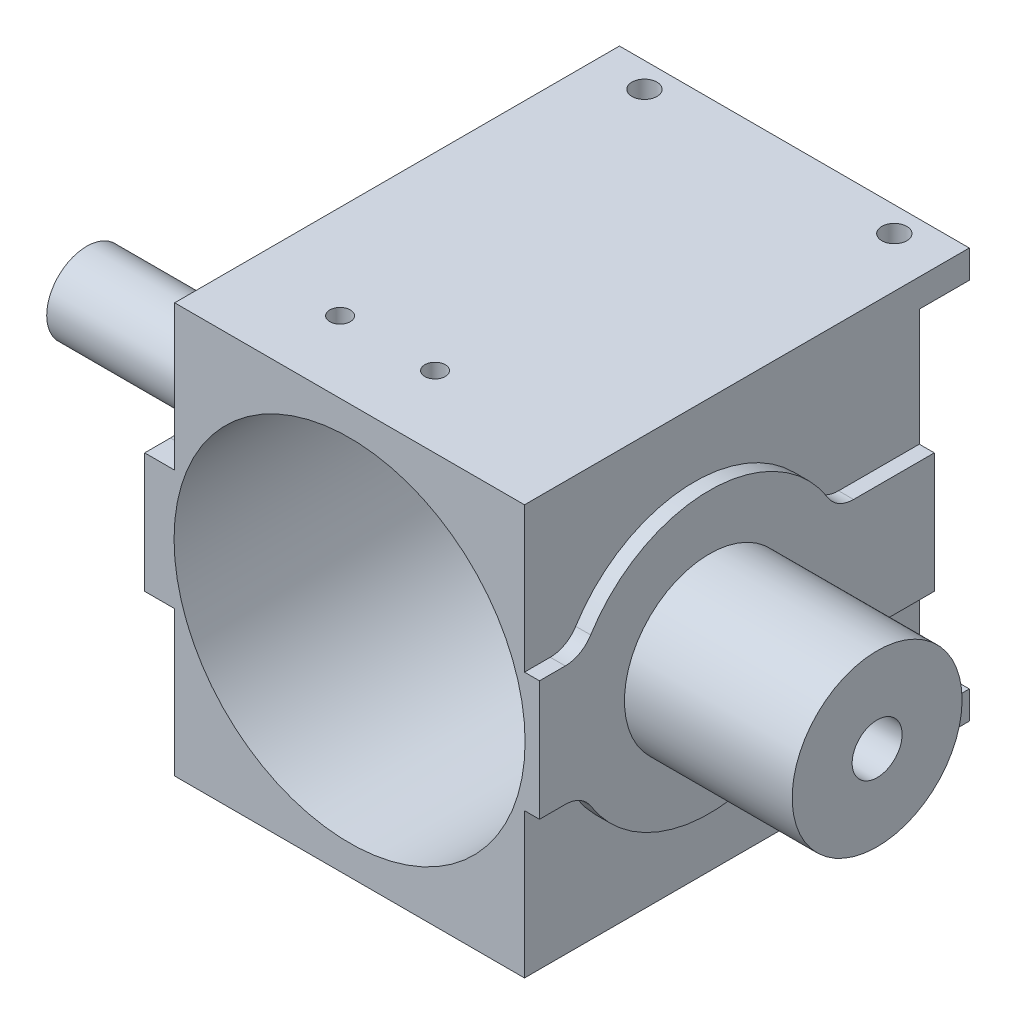
SolidWorks part; units mm, degrees
material "6061 Alloy"
ref_plane "Front Plane" through (0, 0, 0) normal (0, 0, 1) x (1, 0, 0)
ref_plane "Top Plane" through (0, 0, 0) normal (0, 1, 0) x (1, 0, 0)
ref_plane "Right Plane" through (0, 0, 0) normal (1, 0, 0) x (0, 0, -1)
sketch "Sketch1" plane through (0, 0, 0) normal (0, 0, 1) x (1, 0, 0)
  line L0 (-21.7909, 0) -> (22.7272, 0) construction
  line L1 (-17.5, 20.5) -> (17.5, 20.5)
  line L2 (-17.5, 20.5) -> (-17.5, 6)
  line L3 (-17.5, -20.5) -> (17.5, -20.5)
  line L4 (17.5, 20.5) -> (17.5, 6)
  line L5 (-17.5, 20.5) -> (17.5, -20.5) construction
  line L6 (-17.5, -20.5) -> (17.5, 20.5) construction
  line L7 (-17.5, -6) -> (-17.5, -20.5)
  line L8 (-20.5, 6) -> (-17.5, 6)
  line L9 (-20.5, 6) -> (-20.5, -6)
  line L10 (-20.5, -6) -> (-17.5, -6)
  line L12 (-20.5, 6) -> (-17.5, -6) construction
  line L13 (-20.5, -6) -> (-17.5, 6) construction
  line L14 (19, 6) -> (17.5, 6)
  line L15 (19, 6) -> (19, -6)
  line L16 (19, -6) -> (17.5, -6)
  line L18 (19, 6) -> (17.5, -6) construction
  line L19 (19, -6) -> (17.5, 6) construction
  line L20 (17.5, -6) -> (17.5, -20.5)
  point P0 (0, 0)
  point P8 (-19, 0)
  point P13 (18.25, 0)
  dimension "D1" = 41
  dimension "D2" = 35
  dimension "D3" = 12
  dimension "D4" = 12
  dimension "D5" = 1.5
  dimension "D6" = 3
extrude "Boss-Extrude1" add sketch "Sketch1" along normal blind 44.5
sketch "Sketch3" plane through (-17.5, 0, 0) normal (-1, 0, 0) x (0, 0, 1)
  line L0 (44.5, 6) -> (44.5, -6) construction
  circle A0 centre (27.5, 0) radius 14
  dimension "D1" = 28
  dimension "D2" = 17
extrude "Boss-Extrude2" add sketch "Sketch3" along normal up to surface and the other way up to surface up to face at (-20.5, 0, 22.25) other way up to face at (19, 0, 22.25)
sketch "Sketch5" plane through (0, 0, 44.5) normal (0, 0, 1) x (1, 0, 0)
  circle A0 centre (0, 0) radius 17.56
  dimension "D1" = 35.12
extrude "Cut-Extrude2" cut sketch "Sketch5" against normal through all
sketch "Sketch6" plane through (-20.5, 0, 0) normal (-1, 0, 0) x (0, 0, 1)
  line L0 (0, 20.5) -> (0, 6) construction
  line L1 (0, 17.7) -> (5, 17.7)
  line L2 (0, 17.7) -> (0, -17.7)
  line L3 (0, -17.7) -> (5, -17.7)
  line L4 (5, 17.7) -> (5, -17.7)
  line L5 (44.5, 20.5) -> (0, 20.5) construction
  line L6 (44.5, -20.5) -> (0, -20.5) construction
  dimension "D1" = 2.8
  dimension "D2" = 2.8
  dimension "D3" = 35.4
  dimension "D4" = 5
extrude "Cut-Extrude3" cut sketch "Sketch6" against normal through all
fillet "Fillet1" radius 3 8 edges at (18.25, 6, 40.1491) (18.25, 6, 14.8509) (18.25, -6, 14.8509) (18.25, -6, 40.1491) (-19, 6, 40.1491) (-19, 6, 14.8509) (-19, -6, 14.8509) (-19, -6, 40.1491)
sketch "Sketch7" plane through (19, 0, 0) normal (1, 0, 0) x (0, 0, -1)
  circle A0 centre (-27.5, 0) radius 8.5
  dimension "D1" = 17
extrude "Boss-Extrude4" add sketch "Sketch7" along normal blind 16.78
sketch "Sketch8" plane through (-20.5, 0, 0) normal (-1, 0, 0) x (0, 0, 1)
  circle A0 centre (27.5, 0) radius 4
  dimension "D1" = 8
extrude "Boss-Extrude5" add sketch "Sketch8" along normal blind 22.8
chamfer "Chamfer1" distance 1 angle 45 1 edges at (-20.5, 0, 31.5)
hole_wizard "M3x0.5 Tapped Hole1" positions "Sketch9" profile "Sketch11" tap size "M3x0.5" standard "ANSI Metric" end condition through all
sketch "Sketch9" plane through (0, -20.5, 0) normal (0, -1, 0) x (-1, 0, 0)
  line L0 (17.5, 0) -> (-17.5, 0) construction
  line L1 (-17.5, -44.5) -> (-17.5, 0) construction
  line L2 (17.5, -44.5) -> (17.5, 0) construction
  point P0 (-12.5, -2.5)
  point P2 (12.5, -2.5)
  dimension "D1" = 2.5
  dimension "D2" = 5
  dimension "D3" = 5
sketch "Sketch11" plane through (12.5, -20.5, 2.5) normal (1, 0, 0) x (0, 0, -1)
  line L0 (0, 0) -> (0, 41)
  line L1 (0, 41) -> (1.25, 41)
  line L2 (1.25, 41) -> (1.25, 0)
  line L5 (1.25, 0) -> (0, 0)
  line L11 (0, -6.35) -> (0, 107.95) construction
  dimension "Thru Tap Drill Dia." = 2.5
  dimension "Thru Tap Drill Depth" = 41
cosmetic thread "Hole Thread1" parameters "D2"=3
cosmetic thread "Hole Thread2" parameters "D2"=3
hole_wizard "M2.5x0.45 Tapped Hole1" positions "Sketch12" profile "Sketch13" tap size "M2.5x0.45" standard "ANSI Metric"
sketch "Sketch12" plane through (0, 20.5, 0) normal (0, 1, 0) x (1, 0, 0)
  line L0 (17.5, -44.5) -> (-17.5, -44.5) construction
  line L1 (-20.5, -15.6229) -> (-20.5, -39.3771) construction
  point P0 (-8.1, -37.35)
  point P2 (1.4, -37.35)
  dimension "D1" = 9.5
  dimension "D2" = 7.15
  dimension "D3" = 12.4
sketch "Sketch13" plane through (-8.1, 20.5, 37.35) normal (1, 0, 0) x (0, 0, 1)
  line L0 (0, 0) -> (0, 4.9198)
  line L1 (0, 4.9198) -> (1.025, 4.9198)
  line L2 (1.025, 4.9198) -> (1.025, 0)
  line L5 (1.025, 0) -> (0, 0)
  line L11 (0, -6.35) -> (0, 107.95) construction
  dimension "Thru Tap Drill Dia." = 2.05
  dimension "Thru Tap Drill Depth" = 4.9198
cosmetic thread "Hole Thread3" parameters "D2"=2.5
cosmetic thread "Hole Thread4" parameters "D2"=2.5
hole_wizard "M6x1.0 Tapped Hole1" positions "Sketch14" profile "Sketch15" tap size "M6x1.0" standard "ANSI Metric"
sketch "Sketch14" plane through (35.78, 0, 0) normal (1, 0, 0) x (0, 0, -1)
  point P0 (-27.5, 0)
sketch "Sketch15" plane through (35.78, 0, 27.5) normal (0, 1, 0) x (0, 0, -1)
  line L0 (0, 0) -> (0, 11.5022)
  line L1 (0, 11.5022) -> (2.5, 10)
  line L2 (2.5, 10) -> (2.5, 0)
  line L5 (2.5, 0) -> (0, 0)
  line L10 (0, 11.5022) -> (-2.5, 10) construction
  line L11 (0, -6.35) -> (0, 107.95) construction
  dimension "Tap Drill Dia." = 5
  dimension "Tap Drill Depth" = 10
  dimension "Drill Angle" = 118
sketch "Sketch16" plane through (0, 0, 5) normal (0, 0, -1) x (-1, 0, 0)
  line L0 (-17.5, -17.7) -> (17.5, 17.7) construction
  circle A2 centre (12.346, 12.4871) radius 4
  circle A3 centre (0, 0) radius 17.56 construction
  circle A4 centre (12.5223, -12.3105) radius 4
  circle A5 centre (-12.2753, -12.4867) radius 4
  circle A6 centre (-12.4516, 12.3109) radius 4
  point P18 (0.0354, 0.0002)
  dimension "D1" = 4
  dimension "D2" = 8
extrude "Cut-Extrude4" cut sketch "Sketch16" against normal blind 4
